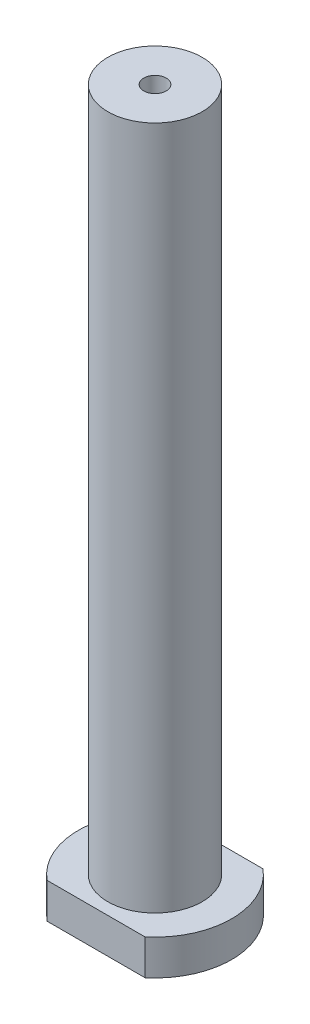
SolidWorks part; units mm, degrees
ref_plane "Front Plane" through (0, 0, 0) normal (0, 0, 1) x (1, 0, 0)
ref_plane "Top Plane" through (0, 0, 0) normal (0, 1, 0) x (1, 0, 0)
ref_plane "Right Plane" through (0, 0, 0) normal (1, 0, 0) x (0, 0, -1)
sketch "Sketch1" plane through (0, 0, 0) normal (0, 1, 0) x (1, 0, 0)
  line L0 (-4.5, 0) -> (1000, 0) construction
  line L1 (-4.1533, -5) -> (4.1533, -5)
  line L2 (-4.1533, 5) -> (4.1533, 5)
  line L3 (-4.5, 5) -> (1000, 5) construction
  line L4 (-4.5, -5) -> (1000, -5) construction
  arc A0 (-4.1533, 5) -> (-4.1533, -5) centre (0, 0) ccw
  arc A1 (4.1533, -5) -> (4.1533, 5) centre (0, 0) ccw
  circle A2 centre (0, 0) radius 0.95
  dimension "D1" = 13
  dimension "D4" = 1.9
  dimension "D2" = 5
  dimension "D3" = 5
extrude "Boss-Extrude1" add sketch "Sketch1" along normal blind 3
sketch "Sketch2" plane through (0, 3, 0) normal (0, 1, 0) x (1, 0, 0)
  circle A0 centre (0, 0) radius 0.95 construction
  circle A1 centre (0, 0) radius 0.95
  circle A2 centre (0, 0) radius 4
  dimension "D1" = 8
extrude "Boss-Extrude2" add sketch "Sketch2" along normal blind 58
